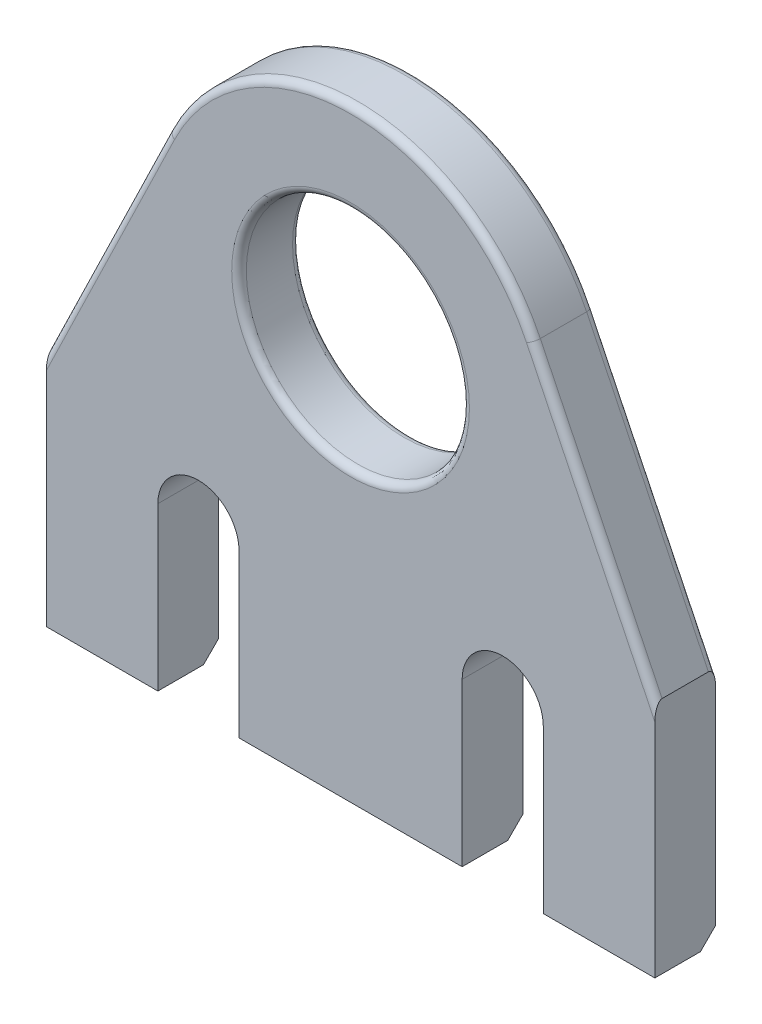
SolidWorks part; units mm, degrees
ref_plane "front" through (0, 0, 0) normal (0, 0, 1) x (1, 0, 0)
ref_plane "top" through (0, 0, 0) normal (0, 1, 0) x (1, 0, 0)
ref_plane "right" through (0, 0, 0) normal (1, 0, 0) x (0, 0, -1)
sketch "Sketch1" plane through (0, 0, 0) normal (0, 0, 1) x (1, 0, 0)
  line L0 (0, 0) -> (0, -50.8) construction
  line L1 (-47.625, -74.6252) -> (-47.625, -142.2683) construction
  line L2 (-60.325, -74.6252) -> (-60.325, -125.4252)
  line L3 (-34.925, -74.6252) -> (-34.925, -125.4252)
  line L4 (-60.325, -125.4252) -> (-95.25, -125.4252)
  line L5 (60.325, -125.4252) -> (95.25, -125.4252)
  line L6 (34.925, -74.6252) -> (34.925, -125.4252)
  line L7 (60.325, -74.6252) -> (60.325, -125.4252)
  line L8 (-34.925, -125.4252) -> (34.925, -125.4252)
  line L9 (-95.25, -125.4252) -> (-95.25, -50.8)
  line L10 (-95.25, -50.8) -> (-57.124, 27.7326)
  line L11 (95.25, -50.8) -> (57.124, 27.7326)
  line L12 (95.25, -125.4252) -> (95.25, -50.8)
  circle A0 centre (0, 0) radius 34.925
  arc A1 (57.124, 27.7326) -> (-57.124, 27.7326) centre (0, 0) ccw
  arc A2 (-34.925, -74.6252) -> (-60.325, -74.6252) centre (-47.625, -74.6252) ccw
  arc A3 (34.925, -74.6252) -> (60.325, -74.6252) centre (47.625, -74.6252) cw
  point P25 (-95.25, -50.8)
  point P28 (95.25, -50.8)
  dimension "D3" = 12.7
  dimension "D5" = 190.5
  dimension "D6" = 69.85
  dimension "D7" = 63.5
  dimension "D8" = 74.6252
  dimension "D10" = 15.875
  dimension "D4" = 63.5
  dimension "D2" = 47.625
  dimension "D9" = 50.8
extrude "Extrude1" add sketch "Sketch1" against normal blind 19.05
ref_plane "locate" through (0, -50.8, 0) normal (0, -1, 0) x (1, 0, 0)
chamfer "Chamfer3" distance 4.7752 angle 45 3 edges at (77.7875, -125.4252, -19.05) (0, -125.4252, -19.05) (-77.7875, -125.4252, -19.05)
fillet "Fillet1" radius 2.286 8 edges at (76.187, -11.5337, 0) (-76.187, -11.5337, 0) (76.187, -11.5337, -19.05) (-76.187, -11.5337, -19.05) (34.925, 0, 0) (34.925, 0, -19.05) (0, 63.5, 0) (0, 63.5, -19.05)
